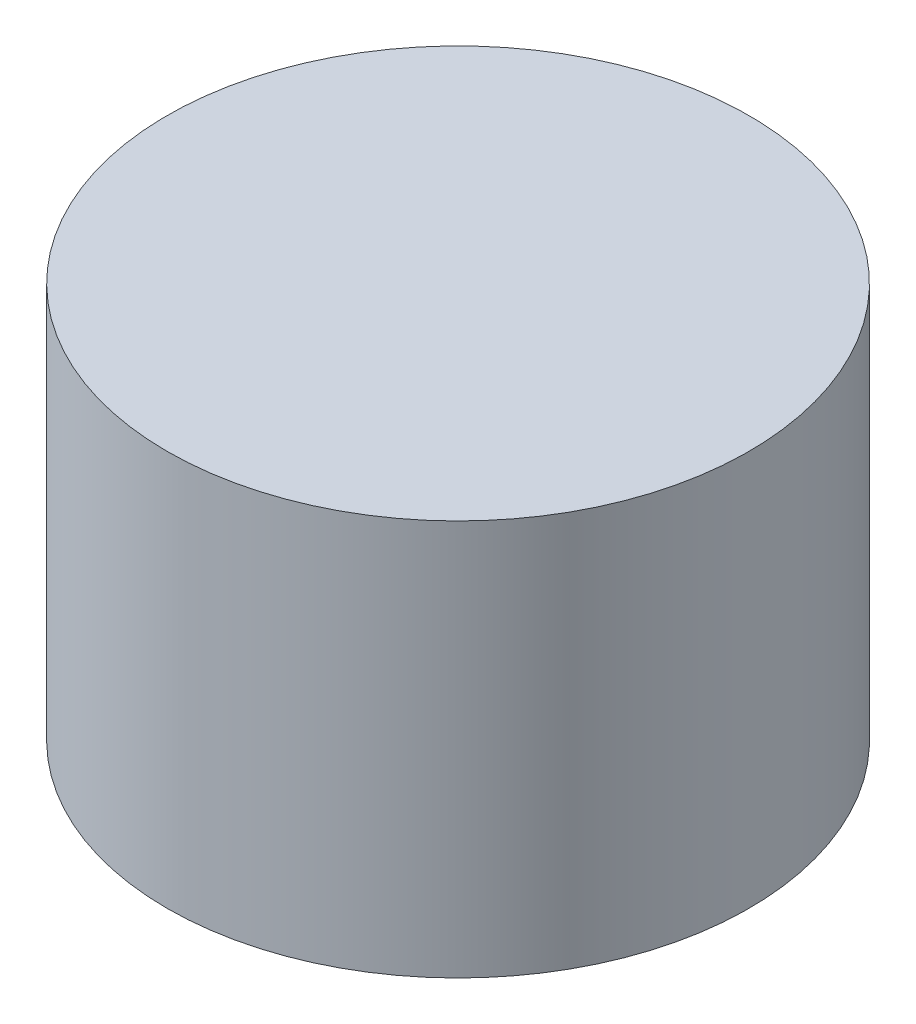
SolidWorks part; units mm, degrees
material "Nailon 101"
ref_plane "Alzado" through (0, 0, 0) normal (0, 0, 1) x (1, 0, 0)
ref_plane "Planta" through (0, 0, 0) normal (0, 1, 0) x (1, 0, 0)
ref_plane "Vista lateral" through (0, 0, 0) normal (1, 0, 0) x (0, 0, -1)
sketch "Croquis1" plane through (0, 0, 0) normal (0, 1, 0) x (1, 0, 0)
  circle A0 centre (0, 0) radius 7.35
  dimension "D1" = 14.7
extrude "Saliente-Extruir1" add sketch "Croquis1" along normal blind 10
